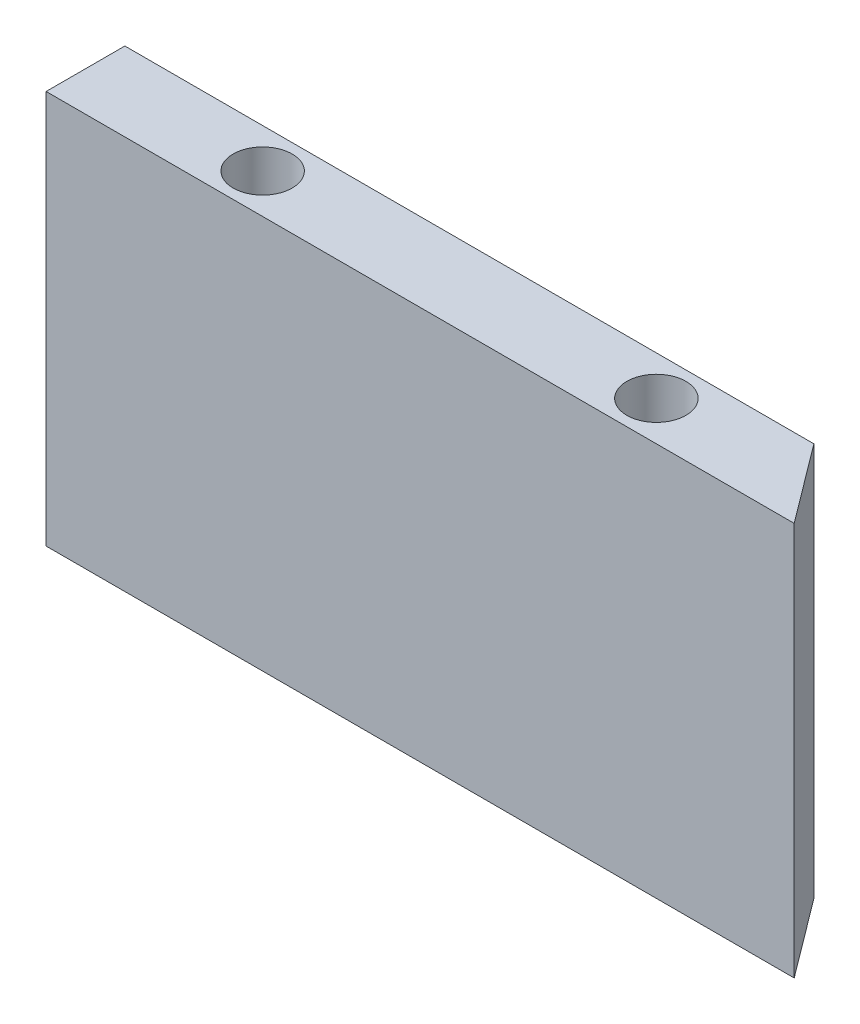
SolidWorks part; units mm, degrees
ref_plane "Front Plane" through (0, 0, 0) normal (0, 0, 1) x (1, 0, 0)
ref_plane "Top Plane" through (0, 0, 0) normal (0, 1, 0) x (1, 0, 0)
ref_plane "Right Plane" through (0, 0, 0) normal (1, 0, 0) x (0, 0, -1)
sketch "Sketch1" plane through (0, 0, 0) normal (0, 1, 0) x (1, 0, 0)
  line L0 (-464.4376, 50.8) -> (424.5624, 50.8)
  line L2 (500.7624, -50.8) -> (-464.4376, -50.8)
  line L3 (-464.4376, -50.8) -> (-464.4376, 50.8)
  line L4 (424.5624, 50.8) -> (500.7624, -50.8)
  dimension "D1" = 889
  dimension "D2" = 965.2
  dimension "D3" = 101.6
extrude "Boss-Extrude2" add sketch "Sketch1" along normal blind 508 contours L2 L3 L0 L4
sketch "Sketch5" plane through (0, 508, 0) normal (0, 1, 0) x (1, 0, 0)
  line L0 (-464.4376, -50.8) -> (-464.4376, 50.8) construction
  circle A0 centre (-235.8376, 0) radius 38.1
  circle A1 centre (272.1624, 0) radius 38.1
  dimension "D3" = 76.2
  dimension "D4" = 76.2
  dimension "D1" = 228.6
  dimension "D2" = 508
extrude "Cut-Extrude1" cut sketch "Sketch5" against normal blind 127
sketch "Sketch7" plane through (0, 0, 0) normal (0, -1, 0) x (1, 0, 0)
  line L0 (-464.4376, 50.8) -> (-464.4376, -50.8) construction
  circle A0 centre (-235.8376, 0) radius 40.8522
  circle A1 centre (272.1624, 0) radius 38.7021
  point P6 (0, 0)
  point P8 (0, 0)
  dimension "D1" = 228.6
  dimension "D2" = 508
extrude "Cut-Extrude2" cut sketch "Sketch7" against normal blind 127
